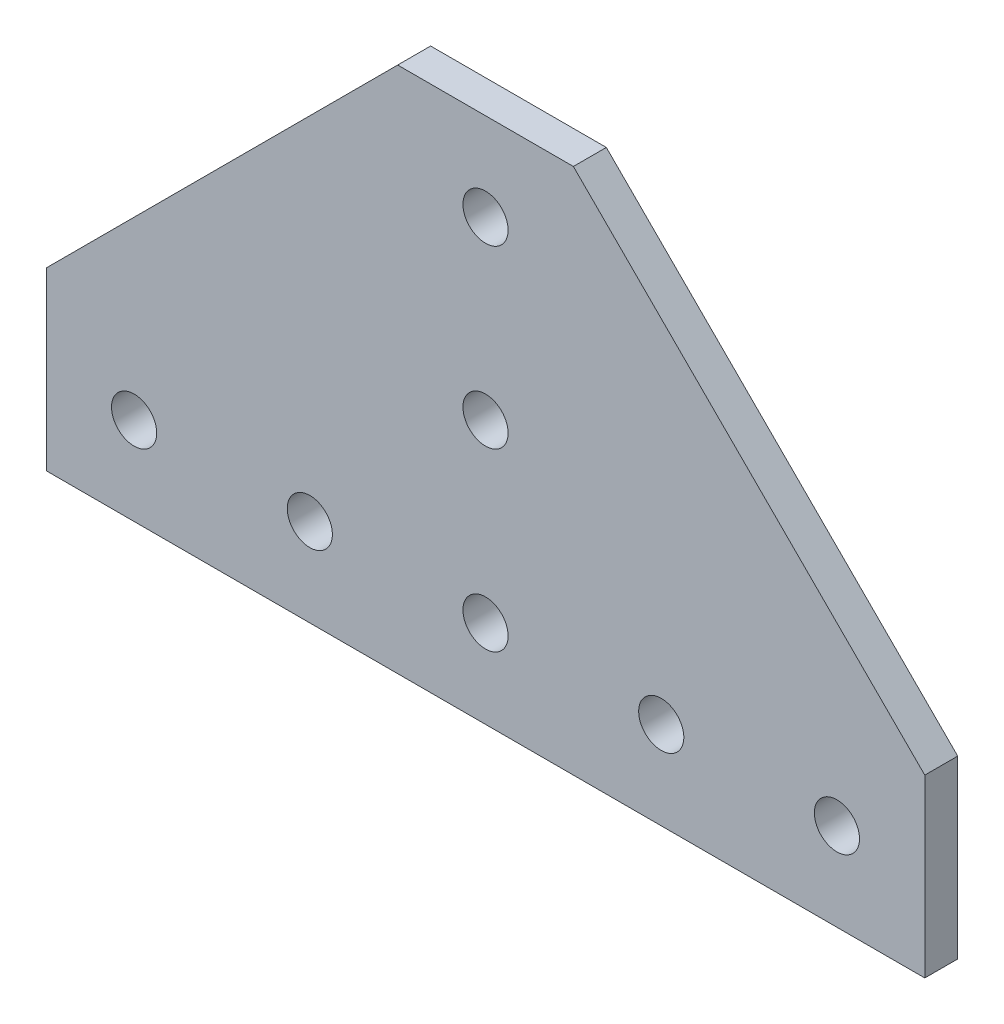
SolidWorks part; units mm, degrees
ref_plane "Front Plane" through (0, 0, 0) normal (0, 0, 1) x (1, 0, 0)
ref_plane "Top Plane" through (0, 0, 0) normal (0, 1, 0) x (1, 0, 0)
ref_plane "Right Plane" through (0, 0, 0) normal (1, 0, 0) x (0, 0, -1)
sketch "Sketch1" plane through (0, 0, 0) normal (0, 0, 1) x (1, 0, 0)
  line L1 (12.7, 12.7) -> (38.1, 12.7) construction
  line L2 (38.1, 12.7) -> (63.5, 12.7) construction
  line L3 (12.7, 12.7) -> (12.7, 38.1) construction
  line L4 (76.2, 25.4) -> (25.4, 76.2)
  line L5 (76.2, 0) -> (0, 0)
  line L6 (12.7, 38.1) -> (12.7, 63.5) construction
  line L7 (76.2, 25.4) -> (76.2, 0)
  line L8 (0, 76.2) -> (25.4, 76.2)
  line L9 (-50.8, 25.4) -> (0, 76.2)
  line L10 (-50.8, 25.4) -> (-50.8, 0)
  line L11 (-50.8, 0) -> (0, 0)
  circle A0 centre (12.7, 12.7) radius 3.2639
  circle A1 centre (38.1, 12.7) radius 3.2639
  circle A2 centre (63.5, 12.7) radius 3.2639
  circle A3 centre (12.7, 38.1) radius 3.2639
  circle A4 centre (12.7, 63.5) radius 3.2639
  circle A5 centre (-38.1, 12.7) radius 3.2639
  circle A6 centre (-12.7, 12.7) radius 3.2639
  dimension "D1" = 25.4
  dimension "E" = 6.5278
  dimension "C" = 25.4
  dimension "D3" = 12.7
  dimension "B" = 76.2
  dimension "D4" = 63.5
extrude "Boss-Extrude1" add sketch "Sketch1" along normal mid plane 4.7625
